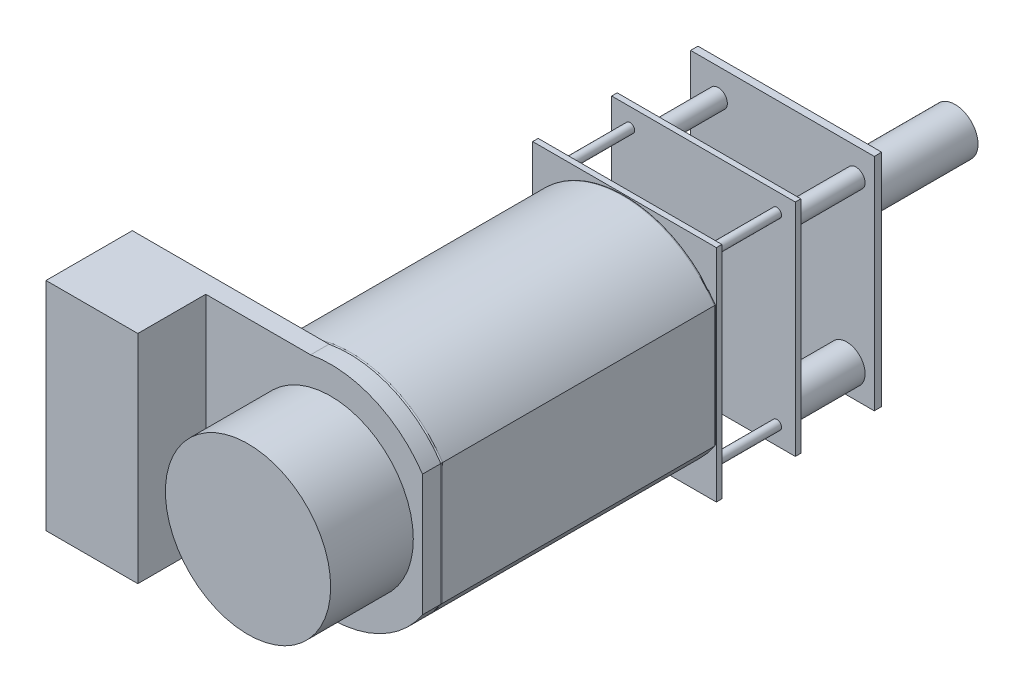
SolidWorks part; units mm, degrees
ref_plane "Front Plane" through (0, 0, 0) normal (0, 0, 1) x (1, 0, 0)
ref_plane "Top Plane" through (0, 0, 0) normal (0, 1, 0) x (1, 0, 0)
ref_plane "Right Plane" through (0, 0, 0) normal (1, 0, 0) x (0, 0, -1)
sketch "Sketch1" plane through (0, 0, 0) normal (0, 0, 1) x (1, 0, 0)
  line L2 (-5, -3.3166) -> (-5, 3.3166)
  line L4 (5, -3.3166) -> (5, 3.3166)
  line L5 (-3.8411, -4.6093) -> (3.8411, 4.6093) construction
  line L6 (-3.8411, 4.6093) -> (3.8411, -4.6093) construction
  arc A0 (-5, -3.3166) -> (5, -3.3166) centre (0, 0) ccw
  arc A1 (5, 3.3166) -> (-5, 3.3166) centre (0, 0) ccw
  point P0 (0, 0)
  dimension "D3" = 12
  dimension "D1" = 5
  dimension "D2" = 3.8411
extrude "Boss-Extrude1" add sketch "Sketch1" along normal blind 15
fillet "Fillet1" radius 0.1 8 edges at (0, -6, 15) (-5, 0, 15) (0, 6, 15) (5, 0, 15) (0, -6, 0) (5, 0, 0) (-5, 0, 0) (0, 6, 0)
sketch "Sketch2" plane through (0, 0, 15) normal (0, 0, 1) x (1, 0, 0)
  circle A0 centre (0, 0) radius 2.5
  dimension "D1" = 5
extrude "Boss-Extrude2" add sketch "Sketch2" along normal blind 1
sketch "Sketch3" plane through (0, 0, 16) normal (0, 0, 1) x (1, 0, 0)
  circle A0 centre (0, 0) radius 1.25
  dimension "D1" = 2.5
extrude "Boss-Extrude3" add sketch "Sketch3" along normal blind 0.1
sketch "Sketch4" plane through (0, 0, 0) normal (0, 0, -1) x (-1, 0, 0)
  line L1 (-5, -6) -> (5, -6)
  line L2 (-5, -6) -> (-5, 6)
  line L3 (-5, 6) -> (5, 6)
  line L4 (5, -6) -> (5, 6)
  line L5 (-5, -6) -> (5, 6) construction
  line L6 (-5, 6) -> (5, -6) construction
  point P0 (0, 0)
  dimension "D1" = 12
  dimension "D2" = 10
extrude "Boss-Extrude4" add sketch "Sketch4" along normal blind 0.3
sketch "Sketch5" plane through (0, 0, -0.3) normal (0, 0, -1) x (-1, 0, 0)
  circle A0 centre (0, 0) radius 0.5
  dimension "D1" = 1
extrude "Boss-Extrude5" add sketch "Sketch5" along normal blind 1
sketch "Sketch6" plane through (0, 0, -0.3) normal (0, 0, -1) x (-1, 0, 0)
  line L0 (-0.1, 1.4967) -> (0, 1.6699)
  line L1 (0, 1.6699) -> (0.1, 1.4967)
  line L2 (0.1688, 1.4905) -> (0.2982, 1.643)
  line L3 (0.2982, 1.643) -> (0.3656, 1.4548)
  line L4 (0.4323, 1.4364) -> (0.5867, 1.5634)
  line L5 (0.5867, 1.5634) -> (0.6195, 1.3661)
  line L6 (0.6818, 1.3361) -> (0.8565, 1.4335)
  line L7 (0.8565, 1.4335) -> (0.8535, 1.2335)
  line L8 (0.9094, 1.1929) -> (1.0987, 1.2575)
  line L9 (1.0987, 1.2575) -> (1.06, 1.0613)
  line L10 (1.1078, 1.0113) -> (1.3056, 1.0411)
  line L11 (1.3056, 1.0411) -> (1.2325, 0.855)
  line L12 (1.2706, 0.7973) -> (1.4705, 0.7913)
  line L13 (1.4705, 0.7913) -> (1.3653, 0.6212)
  line L14 (1.3925, 0.5576) -> (1.5881, 0.516)
  line L15 (1.5881, 0.516) -> (1.4543, 0.3674)
  line L16 (1.4697, 0.3) -> (1.6548, 0.2242)
  line L17 (1.6548, 0.2242) -> (1.4965, 0.1018)
  line L18 (1.4996, 0.0328) -> (1.6682, -0.0749)
  line L19 (1.6682, -0.0749) -> (1.4907, -0.167)
  line L20 (1.4814, -0.2355) -> (1.628, -0.3716)
  line L21 (1.628, -0.3716) -> (1.4369, -0.4305)
  line L22 (1.4155, -0.4963) -> (1.5355, -0.6563)
  line L23 (1.5355, -0.6563) -> (1.3369, -0.6802)
  line L24 (1.3042, -0.741) -> (1.3936, -0.9199)
  line L25 (1.3936, -0.9199) -> (1.194, -0.908)
  line L26 (1.1509, -0.962) -> (1.207, -1.154)
  line L27 (1.207, -1.154) -> (1.0127, -1.1066)
  line L28 (0.9606, -1.152) -> (0.9815, -1.351)
  line L29 (0.9815, -1.351) -> (0.7988, -1.2696)
  line L30 (0.7395, -1.3051) -> (0.7245, -1.5045)
  line L31 (0.7245, -1.5045) -> (0.5593, -1.3918)
  line L32 (0.4946, -1.4161) -> (0.4442, -1.6097)
  line L33 (0.4442, -1.6097) -> (0.3018, -1.4693)
  line L34 (0.2338, -1.4817) -> (0.1497, -1.6631)
  line L35 (0.1497, -1.6631) -> (0.0346, -1.4996)
  line L36 (-0.0346, -1.4996) -> (-0.1497, -1.6631)
  line L37 (-0.1497, -1.6631) -> (-0.2338, -1.4817)
  line L38 (-0.3018, -1.4693) -> (-0.4442, -1.6097)
  line L39 (-0.4442, -1.6097) -> (-0.4946, -1.4161)
  line L40 (-0.5593, -1.3918) -> (-0.7245, -1.5045)
  line L41 (-0.7245, -1.5045) -> (-0.7395, -1.3051)
  line L42 (-0.7988, -1.2696) -> (-0.9815, -1.351)
  line L43 (-0.9815, -1.351) -> (-0.9606, -1.152)
  line L44 (-1.0127, -1.1066) -> (-1.207, -1.154)
  line L45 (-1.207, -1.154) -> (-1.1509, -0.962)
  line L46 (-1.194, -0.908) -> (-1.3936, -0.9199)
  line L47 (-1.3936, -0.9199) -> (-1.3042, -0.741)
  line L48 (-1.3369, -0.6802) -> (-1.5355, -0.6563)
  line L49 (-1.5355, -0.6563) -> (-1.4155, -0.4963)
  line L50 (-1.4369, -0.4305) -> (-1.628, -0.3716)
  line L51 (-1.628, -0.3716) -> (-1.4814, -0.2355)
  line L52 (-1.4907, -0.167) -> (-1.6682, -0.0749)
  line L53 (-1.6682, -0.0749) -> (-1.4996, 0.0328)
  line L54 (-1.4965, 0.1018) -> (-1.6548, 0.2242)
  line L55 (-1.6548, 0.2242) -> (-1.4697, 0.3)
  line L56 (-1.4543, 0.3674) -> (-1.5881, 0.516)
  line L57 (-1.5881, 0.516) -> (-1.3925, 0.5576)
  line L58 (-1.3653, 0.6212) -> (-1.4705, 0.7913)
  line L59 (-1.4705, 0.7913) -> (-1.2706, 0.7973)
  line L60 (-1.2325, 0.855) -> (-1.3056, 1.0411)
  line L61 (-1.3056, 1.0411) -> (-1.1078, 1.0113)
  line L62 (-1.06, 1.0613) -> (-1.0987, 1.2575)
  line L63 (-1.0987, 1.2575) -> (-0.9094, 1.1929)
  line L64 (-0.8535, 1.2335) -> (-0.8565, 1.4335)
  line L65 (-0.8565, 1.4335) -> (-0.6818, 1.3361)
  line L66 (-0.6195, 1.3661) -> (-0.5867, 1.5634)
  line L67 (-0.5867, 1.5634) -> (-0.4323, 1.4364)
  line L68 (-0.3656, 1.4548) -> (-0.2982, 1.643)
  line L69 (-0.2982, 1.643) -> (-0.1688, 1.4905)
  circle A0 centre (0, 0) radius 0.5
  arc A1 (-1.06, 1.0613) -> (-1.1078, 1.0113) centre (0, 0) ccw
  arc A2 (-0.8535, 1.2335) -> (-0.9094, 1.1929) centre (0, 0) ccw
  arc A3 (-0.6195, 1.3661) -> (-0.6818, 1.3361) centre (0, 0) ccw
  arc A4 (-0.3656, 1.4548) -> (-0.4323, 1.4364) centre (0, 0) ccw
  arc A5 (-0.1, 1.4967) -> (-0.1688, 1.4905) centre (0, 0) ccw
  arc A6 (0.1688, 1.4905) -> (0.1, 1.4967) centre (0, 0) ccw
  arc A7 (0.4323, 1.4364) -> (0.3656, 1.4548) centre (0, 0) ccw
  arc A8 (0.6818, 1.3361) -> (0.6195, 1.3661) centre (0, 0) ccw
  arc A9 (0.9094, 1.1929) -> (0.8535, 1.2335) centre (0, 0) ccw
  arc A10 (1.1078, 1.0113) -> (1.06, 1.0613) centre (0, 0) ccw
  arc A11 (1.2706, 0.7973) -> (1.2325, 0.855) centre (0, 0) ccw
  arc A12 (1.3925, 0.5576) -> (1.3653, 0.6212) centre (0, 0) ccw
  arc A13 (1.4697, 0.3) -> (1.4543, 0.3674) centre (0, 0) ccw
  arc A14 (1.4996, 0.0328) -> (1.4965, 0.1018) centre (0, 0) ccw
  arc A15 (1.4814, -0.2355) -> (1.4907, -0.167) centre (0, 0) ccw
  arc A16 (1.4155, -0.4963) -> (1.4369, -0.4305) centre (0, 0) ccw
  arc A17 (1.3042, -0.741) -> (1.3369, -0.6802) centre (0, 0) ccw
  arc A18 (1.1509, -0.962) -> (1.194, -0.908) centre (0, 0) ccw
  arc A19 (0.9606, -1.152) -> (1.0127, -1.1066) centre (0, 0) ccw
  arc A20 (0.7395, -1.3051) -> (0.7988, -1.2696) centre (0, 0) ccw
  arc A21 (0.4946, -1.4161) -> (0.5593, -1.3918) centre (0, 0) ccw
  arc A22 (0.2338, -1.4817) -> (0.3018, -1.4693) centre (0, 0) ccw
  arc A23 (-0.0346, -1.4996) -> (0.0346, -1.4996) centre (0, 0) ccw
  arc A24 (-0.3018, -1.4693) -> (-0.2338, -1.4817) centre (0, 0) ccw
  arc A25 (-0.5593, -1.3918) -> (-0.4946, -1.4161) centre (0, 0) ccw
  arc A26 (-0.7988, -1.2696) -> (-0.7395, -1.3051) centre (0, 0) ccw
  arc A27 (-1.0127, -1.1066) -> (-0.9606, -1.152) centre (0, 0) ccw
  arc A28 (-1.194, -0.908) -> (-1.1509, -0.962) centre (0, 0) ccw
  arc A29 (-1.3369, -0.6802) -> (-1.3042, -0.741) centre (0, 0) ccw
  arc A30 (-1.4369, -0.4305) -> (-1.4155, -0.4963) centre (0, 0) ccw
  arc A31 (-1.4907, -0.167) -> (-1.4814, -0.2355) centre (0, 0) ccw
  arc A32 (-1.4965, 0.1018) -> (-1.4996, 0.0328) centre (0, 0) ccw
  arc A33 (-1.4543, 0.3674) -> (-1.4697, 0.3) centre (0, 0) ccw
  arc A34 (-1.3653, 0.6212) -> (-1.3925, 0.5576) centre (0, 0) ccw
  arc A35 (-1.2325, 0.855) -> (-1.2706, 0.7973) centre (0, 0) ccw
  point P112 (0, 0)
  dimension "D1" = 1
  dimension "D2" = 3
  dimension "D3" = 0.2
  dimension "D4" = 0.2
  dimension "D5" = 60
  dimension "D6" = 35
extrude "Boss-Extrude6" add sketch "Sketch6" along normal blind 0.5
sketch "Sketch8" plane through (0, 0, -0.3) normal (0, 0, -1) x (-1, 0, 0)
  line L0 (5, -6) -> (5, 6) construction
  line L1 (-5, -6) -> (5, -6) construction
  line L2 (-5, 6) -> (-5, -6) construction
  circle A0 centre (-4, 5) radius 0.25
  circle A1 centre (4, 5) radius 0.25
  circle A2 centre (4, -5) radius 0.25
  circle A3 centre (-4, -5) radius 0.25
  dimension "D4" = 0.5
  dimension "D1" = 10
  dimension "D2" = 1
  dimension "D3" = 1
  dimension "D5" = 1
extrude "Boss-Extrude7" add sketch "Sketch8" along normal blind 4
sketch "Sketch9" plane through (0, 0, -4.3) normal (0, 0, -1) x (-1, 0, 0)
  line L1 (-5, -6) -> (5, -6)
  line L2 (-5, -6) -> (-5, 6)
  line L3 (-5, 6) -> (5, 6)
  line L4 (5, -6) -> (5, 6)
  line L5 (-5, -6) -> (5, 6) construction
  line L6 (-5, 6) -> (5, -6) construction
  point P0 (0, 0)
extrude "Boss-Extrude8" add sketch "Sketch9" along normal blind 0.3
sketch "Sketch10" plane through (0, 0, -4.6) normal (0, 0, -1) x (-1, 0, 0)
  line L0 (5, 6) -> (-5, 6) construction
  line L1 (-5, 6) -> (-5, -6) construction
  line L2 (-5, -6) -> (5, -6) construction
  line L3 (5, -6) -> (5, 6) construction
  circle A0 centre (-4, 4.5) radius 0.5
  circle A1 centre (-3.5, -4.5) radius 1
  circle A2 centre (3.5, 4.5) radius 0.5
  dimension "D5" = 2
  dimension "D6" = 1
  dimension "D7" = 1
  dimension "D8" = 1.5
  dimension "D1" = 1.5
  dimension "D2" = 1
  dimension "D3" = 1.5
  dimension "D4" = 1.5
extrude "Boss-Extrude9" add sketch "Sketch10" along normal blind 4
sketch "Sketch11" plane through (0, 0, -8.6) normal (0, 0, -1) x (-1, 0, 0)
  line L1 (-5, -6) -> (5, -6)
  line L2 (-5, -6) -> (-5, 6)
  line L3 (-5, 6) -> (5, 6)
  line L4 (5, -6) -> (5, 6)
  line L5 (-5, -6) -> (5, 6) construction
  line L6 (-5, 6) -> (5, -6) construction
  point P0 (0, 0)
extrude "Boss-Extrude10" add sketch "Sketch11" along normal blind 0.4
sketch "Sketch14" plane through (0, 0, -9) normal (0, 0, -1) x (-1, 0, 0)
  circle A0 centre (0, 0) radius 1.25
  dimension "D1" = 2.5
extrude "Boss-Extrude11" add sketch "Sketch14" along normal blind 9
sketch "Sketch15" plane through (0, 0, -9) normal (0, 0, -1) x (-1, 0, 0)
  circle A0 centre (0, 0) radius 1.5
  dimension "D1" = 3
extrude "Boss-Extrude12" add sketch "Sketch15" along normal blind 0.8
sketch "Sketch16" plane through (0, 0, 15) normal (0, 0, 1) x (1, 0, 0)
  line L0 (-4.9, 3.2863) -> (-4.9, -3.2863) construction
  line L4 (5, -3.3166) -> (5, 3.3166)
  line L5 (-3.8411, -4.6093) -> (3.8411, 4.6093) construction
  line L6 (-3.8411, 4.6093) -> (3.8411, -4.6093) construction
  line L8 (-1.0909, -5.9) -> (-11.8, -5.9)
  line L10 (-1.0909, 5.9) -> (-11.8, 5.9)
  line L11 (-11.8, -5.9) -> (-11.8, 5.9)
  arc A0 (-1.0909, -5.9) -> (5, -3.3166) centre (0, 0) ccw
  arc A1 (5, 3.3166) -> (-1.0909, 5.9) centre (0, 0) ccw
  point P0 (0, 0)
  point P6 (0, 0)
  dimension "D1" = 12
  dimension "D2" = 1.0589
  dimension "D3" = 9.9
  dimension "D4" = 6.8
  dimension "D5" = 11.8
  dimension "D6" = 1.0909
extrude "Boss-Extrude13" add sketch "Sketch16" along normal blind 1
sketch "Sketch17" plane through (0, 0, 16) normal (0, 0, 1) x (1, 0, 0)
  circle A0 centre (0, 0) radius 4.5
  dimension "D1" = 9
extrude "Boss-Extrude14" add sketch "Sketch17" along normal blind 4.5
sketch "Sketch18" plane through (0, 0, 16) normal (0, 0, 1) x (1, 0, 0)
  line L0 (-11.8, -5.9) -> (-1.0909, -5.9) construction
  line L1 (-11.8, 5.9) -> (-6.8, 5.9)
  line L2 (-11.8, 5.9) -> (-11.8, -5.9)
  line L3 (-11.8, -5.9) -> (-6.8, -5.9)
  line L4 (-6.8, 5.9) -> (-6.8, -5.9)
  dimension "D1" = 5
extrude "Boss-Extrude15" add sketch "Sketch18" along normal blind 3.7
sketch "Sketch19" plane through (-11.8, 0, 0) normal (-1, 0, 0) x (0, 0, 1)
  line L0 (19.7, 5.9) -> (15, 5.9) construction
  line L1 (19.6, 5.8) -> (15.5, 5.8)
  line L2 (19.6, 5.8) -> (19.6, -5.8)
  line L3 (19.6, -5.8) -> (15.5, -5.8)
  line L4 (15.5, 5.8) -> (15.5, -5.8)
  line L5 (19.7, -5.9) -> (15, -5.9) construction
  line L6 (19.7, 5.9) -> (19.7, -5.9) construction
  line L7 (15, 5.9) -> (15, -5.9) construction
  dimension "D1" = 0.1
  dimension "D2" = 0.1
  dimension "D3" = 0.1
  dimension "D4" = 0.5
extrude "Cut-Extrude1" cut sketch "Sketch19" against normal blind 3.2
